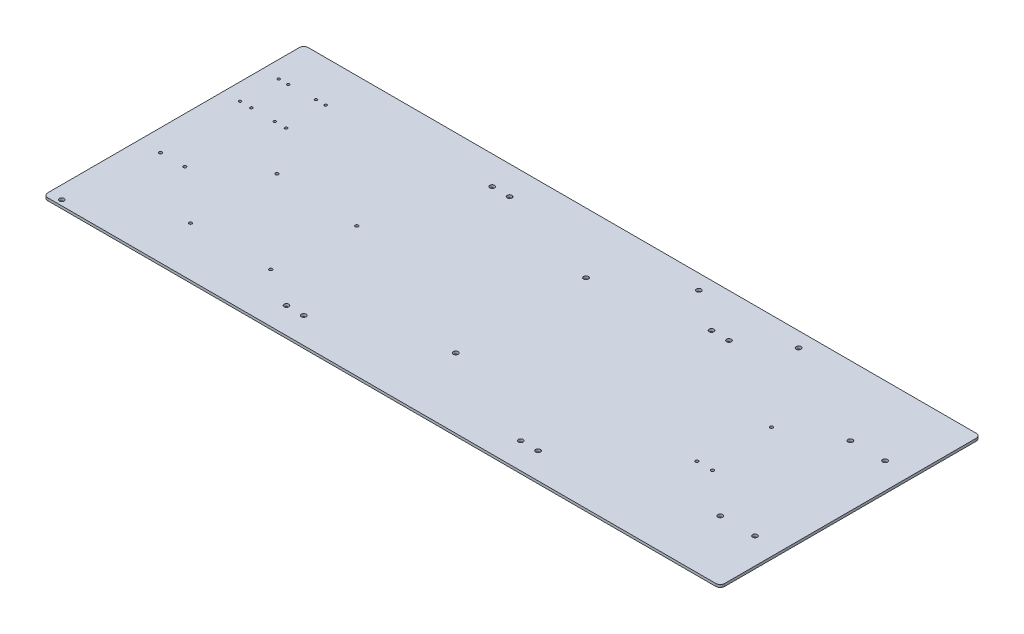
SolidWorks part; units mm, degrees
ref_plane "Front Plane" through (0, 0, 0) normal (0, 0, 1) x (1, 0, 0)
ref_plane "Top Plane" through (0, 0, 0) normal (0, 1, 0) x (1, 0, 0)
ref_plane "Right Plane" through (0, 0, 0) normal (1, 0, 0) x (0, 0, -1)
sketch "Sketch2" plane through (0, 0, 0) normal (0, 1, 0) x (1, 0, 0)
  line L1 (-390, 150) -> (390, 150)
  line L2 (-390, 150) -> (-390, -150)
  line L3 (-390, -150) -> (390, -150)
  line L4 (390, 150) -> (390, -150)
  dimension "D1" = 780
  dimension "D2" = 300
  dimension "D3" = 390
  dimension "D4" = 150
extrude "Boss-Extrude1" add sketch "Sketch2" along normal blind 3
fillet "Fillet1" radius 5 4 edges at (390, 1.5, -150) (390, 1.5, 150) (-390, 1.5, 150) (-390, 1.5, -150)
sketch "Sketch4" plane through (0, 3, 0) normal (0, 1, 0) x (1, 0, 0)
  line L0 (-385, -150) -> (385, -150) construction
  line L1 (390, -145) -> (390, 145) construction
  line L2 (385, 150) -> (-385, 150) construction
  line L5 (-390, 145) -> (-390, -145) construction
  circle A14 centre (5, 80.2954) radius 2.75
  circle A15 centre (5, -69.8031) radius 2.75
  circle A18 centre (82.5, 132.8053) radius 2.75
  circle A19 centre (197.5, 132.8053) radius 2.75
  circle A20 centre (130, 100) radius 2.75
  circle A21 centre (150, 100) radius 2.75
  circle A29 centre (-276.9, 6) radius 1.75
  circle A30 centre (-178.9, 0) radius 1.75
  circle A31 centre (-185, -93) radius 1.75
  circle A32 centre (-277.5, -93) radius 1.75
  circle A44 centre (360, -80) radius 2.75
  circle A49 centre (270, -38.9289) radius 1.75
  circle A52 centre (261, 38.0711) radius 1.75
  circle A55 centre (-328.2929, 102.4906) radius 1.5
  circle A56 centre (-317.2929, 102.4906) radius 1.5
  circle A57 centre (-330.2929, 56.8488) radius 1.5
  circle A58 centre (-317.2929, 56.8488) radius 1.5
  circle A59 centre (-370.5066, 57.1449) radius 1.5
  circle A60 centre (-357.5066, 57.1449) radius 1.5
  circle A63 centre (-365, -40) radius 1.75
  circle A64 centre (-337.1, -40) radius 1.75
  circle A65 centre (-375, -144) radius 2.75
  circle A68 centre (-140, -120) radius 2.75
  circle A69 centre (-120, -120) radius 2.75
  circle A70 centre (360, 70) radius 2.75
  circle A74 centre (130, -120) radius 2.75
  circle A75 centre (150, -120) radius 2.75
  circle A80 centre (320, -80) radius 2.75
  circle A81 centre (320, 70) radius 2.75
  circle A82 centre (252, -38.9289) radius 1.75
  circle A87 centre (-140, 117.1874) radius 2.75
  circle A88 centre (-120, 117.1874) radius 2.75
  circle A89 centre (-370.5066, 101.6105) radius 1.5
  circle A90 centre (-359.5066, 101.6105) radius 1.5
  point P0 (-357.5066, 101.6105)
  dimension "D1" = 150
  dimension "D6" = 77
  dimension "D8" = 50
  dimension "D9" = 9
  dimension "D12" = 115
  dimension "D26" = 92.5
  dimension "D27" = 93
  dimension "D31" = 13
  dimension "D34" = 112.5
  dimension "D2" = 30
  dimension "D3" = 150
  dimension "D4" = 40
  dimension "D5" = 80
  dimension "D7" = 240
  dimension "D10" = 18
  dimension "D11" = 20
  dimension "D13" = 47.5
  dimension "D14" = 50
  dimension "D15" = 30
  dimension "D16" = 45
  dimension "D17" = 27.9
  dimension "D18" = 25
  dimension "D19" = 110
  dimension "D20" = 13
  dimension "D21" = 125
  dimension "D22" = 20
  dimension "D23" = 250
  dimension "D24" = 20
  dimension "D25" = 30
  dimension "D28" = 99
  dimension "D29" = 98
  dimension "D30" = 150
  dimension "D32" = 11
  dimension "D33" = 11
  dimension "D35" = 0.6
  dimension "D36" = 6
  dimension "D37" = 15
extrude "Cut-Extrude3" cut sketch "Sketch4" against normal blind 10
